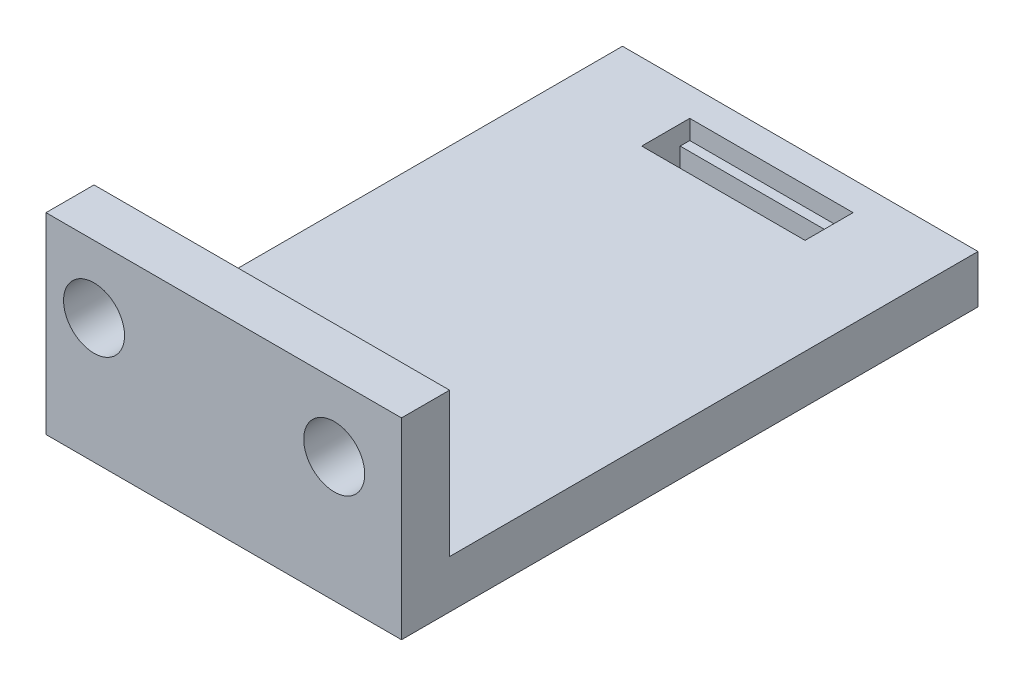
SolidWorks part; units mm, degrees
ref_plane "Front Plane" through (0, 0, 0) normal (0, 0, 1) x (1, 0, 0)
ref_plane "Top Plane" through (0, 0, 0) normal (0, 1, 0) x (1, 0, 0)
ref_plane "Right Plane" through (0, 0, 0) normal (1, 0, 0) x (0, 0, -1)
sketch "Sketch1" plane through (0, 0, 0) normal (0, 1, 0) x (1, 0, 0)
  line L1 (0, 0) -> (37, 0)
  line L2 (0, 0) -> (0, -55)
  line L3 (0, -55) -> (37, -55)
  line L4 (37, 0) -> (37, -55)
  line L5 (10, -4) -> (27, -4)
  line L6 (10, -4) -> (10, -7)
  line L7 (10, -7) -> (27, -7)
  line L8 (27, -4) -> (27, -7)
  dimension "D1" = 17
  dimension "D2" = 3
  dimension "D3" = 10
  dimension "D4" = 10
  dimension "D5" = 48
  dimension "D6" = 55
extrude "Boss-Extrude1" add sketch "Sketch1" along normal blind 3
sketch "Sketch2" plane through (0, 0, 55) normal (0, 0, 1) x (1, 0, 0)
  line L0 (0, 3) -> (0, 0) construction
  line L1 (0, 0) -> (37, 0)
  line L3 (0, 20) -> (37, 20)
  line L5 (0, 0) -> (0, 20)
  line L7 (37, 0) -> (37, 20)
  circle A0 centre (5, 13) radius 3.175
  circle A1 centre (30, 13) radius 3.175
  dimension "D1" = 6.35
  dimension "D2" = 6.35
  dimension "D3" = 5
  dimension "25" = 25
  dimension "D4" = 20
  dimension "D5" = 7
extrude "Boss-Extrude2" add sketch "Sketch2" along normal blind 5
sketch "Sketch3" plane through (0, 3, 0) normal (0, 1, 0) x (1, 0, 0)
  line L0 (10, -3) -> (27, -3)
  line L1 (0, 0) -> (37, 0)
  line L2 (0, 0) -> (0, -55)
  line L3 (0, -55) -> (37, -55)
  line L4 (37, 0) -> (37, -55)
  line L5 (27, -3) -> (27, -8)
  line L6 (27, -8) -> (10, -8)
  line L7 (10, -8) -> (10, -3)
  line L8 (27, -4) -> (10, -4) construction
  line L9 (10, -7) -> (27, -7) construction
  line L10 (27, -7) -> (27, -4) construction
  dimension "D1" = 1
  dimension "D2" = 1
extrude "Boss-Extrude3" add sketch "Sketch3" along normal blind 2
